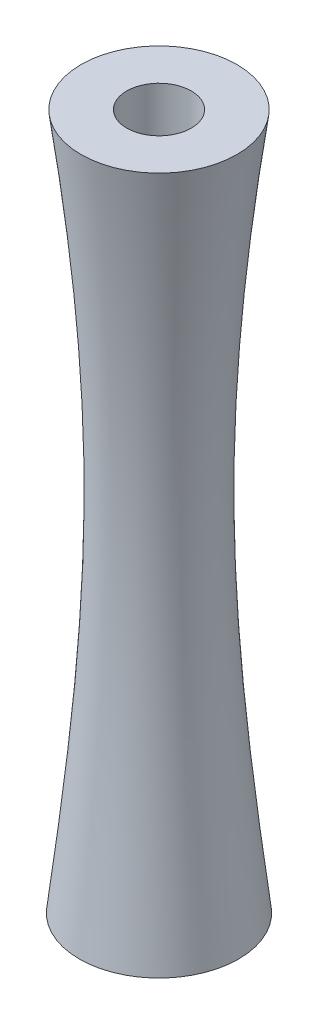
SolidWorks part; units mm, degrees
ref_plane "Front Plane" through (0, 0, 0) normal (0, 0, 1) x (1, 0, 0)
ref_plane "Top Plane" through (0, 0, 0) normal (0, 1, 0) x (1, 0, 0)
ref_plane "Right Plane" through (0, 0, 0) normal (1, 0, 0) x (0, 0, -1)
sketch "Sketch3" plane through (0, 0, 0) normal (0, 0, 1) x (1, 0, 0)
  line L0 (-7.4095, 31.8912) -> (0, 31.8912)
  line L1 (0, 31.8912) -> (0, -32.8467)
  line L2 (-7.2521, 31.8912) -> (0.1574, 31.8912)
  line L3 (0, -32.8467) -> (-7.4095, -32.8467)
  line L4 (0.1574, 31.8912) -> (7.5669, 31.8912)
  line L5 (0, -32.8467) -> (7.4095, -32.8467)
  spline S0 degree 3 poles (-7.2521, 31.8912) (-3.6604, 6.1181) (-4.6604, -9.9147) (-7.4095, -32.8467) knots 0 0 0 0 1 1 1 1
  spline S1 degree 3 poles (7.2521, 31.8912) (3.6604, 6.1181) (4.6604, -9.9147) (7.4095, -32.8467) knots 0 0 0 0 1 1 1 1
revolve "Revolve1" add sketch "Sketch3" angle 360 about L1
sketch "Sketch4" plane through (0, 31.8912, 0) normal (0, 1, 0) x (1, 0, 0)
  circle A0 centre (0, 0) radius 3
extrude "Cut-Extrude1" cut sketch "Sketch4" against normal through all
